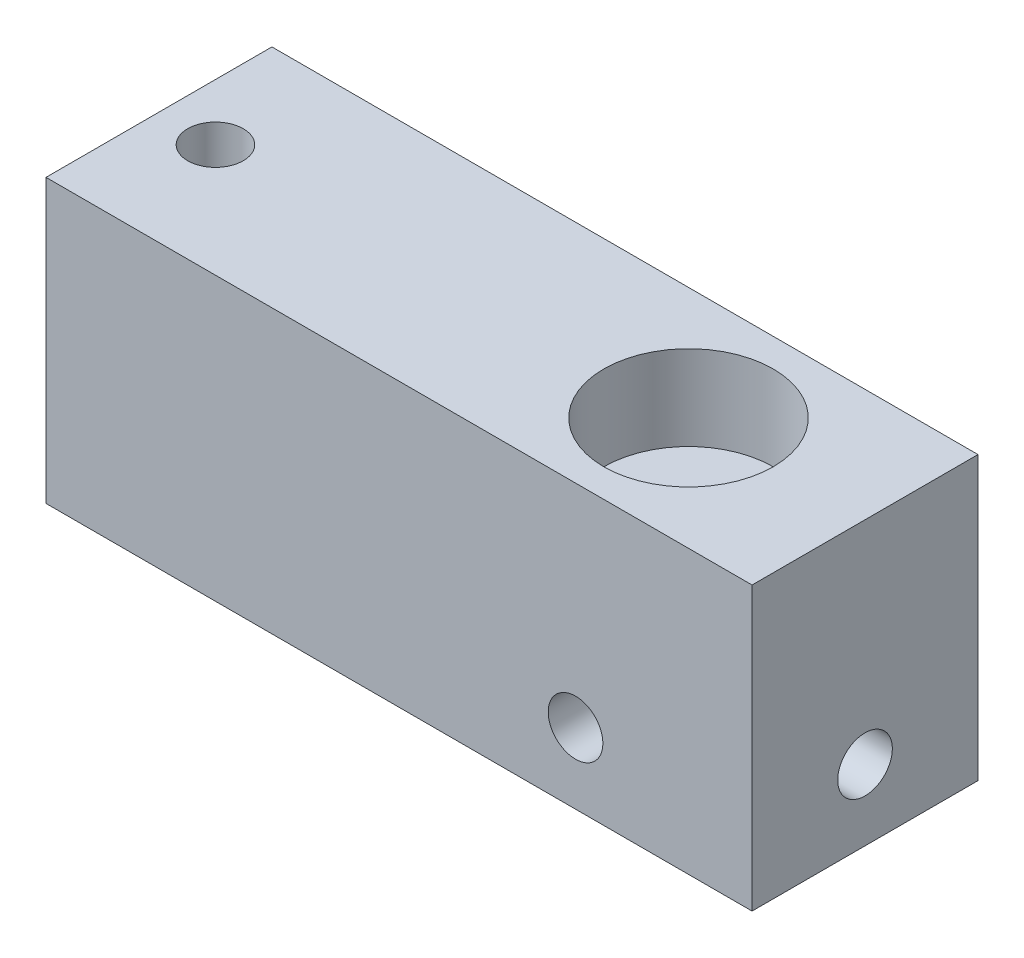
SolidWorks part; units mm, degrees
ref_plane "Front Plane" through (0, 0, 0) normal (0, 0, 1) x (1, 0, 0)
ref_plane "Top Plane" through (0, 0, 0) normal (0, 1, 0) x (1, 0, 0)
ref_plane "Right Plane" through (0, 0, 0) normal (1, 0, 0) x (0, 0, -1)
sketch "Sketch1" plane through (0, 0, 0) normal (0, 0, 1) x (1, 0, 0)
  line L1 (-48.5353, 3.7388) -> (14.9647, 3.7388)
  line L2 (-48.5353, 3.7388) -> (-48.5353, -21.6612)
  line L3 (-48.5353, -21.6612) -> (14.9647, -21.6612)
  line L4 (14.9647, 3.7388) -> (14.9647, -21.6612)
  dimension "D1" = 63.5
  dimension "D2" = 25.4
extrude "Boss-Extrude1" add sketch "Sketch1" along normal blind 20.32
hole_wizard "#10 (0.1935) Diameter Hole1" positions "Sketch2" profile "Sketch3" hole size "#10" standard "ANSI Inch"
sketch "Sketch2" plane through (14.9647, 0, 0) normal (1, 0, 0) x (0, 0, -1)
  line L0 (-20.32, -21.6612) -> (-20.32, 3.7388) construction
  line L2 (-20.32, -21.6612) -> (0, -21.6612) construction
  point P0 (-10.16, -15.3112)
  dimension "D1" = 10.16
  dimension "D2" = 6.35
sketch "Sketch3" plane through (14.9647, -15.3112, 10.16) normal (0, 1, 0) x (0, 0, -1)
  line L0 (0, 0) -> (0, 17.3516)
  line L1 (0, 17.3516) -> (2.4574, 15.875)
  line L2 (2.4574, 15.875) -> (2.4574, 0)
  line L5 (2.4574, 0) -> (0, 0)
  line L10 (0, 17.3516) -> (-2.4575, 15.875) construction
  line L11 (0, -6.35) -> (0, 107.95) construction
  dimension "Hole Dia." = 4.9149
  dimension "Hole Depth" = 15.875
  dimension "Drill Angle" = 118
hole_wizard "#10 (0.1935) Diameter Hole2" positions "Sketch4" profile "Sketch5" hole size "#10" standard "ANSI Inch"
sketch "Sketch4" plane through (0, 0, 20.32) normal (0, 0, 1) x (1, 0, 0)
  line L0 (-48.5353, -21.6612) -> (14.9647, -21.6612) construction
  line L1 (14.9647, -21.6612) -> (14.9647, 3.7388) construction
  point P0 (-0.9103, -15.3112)
  dimension "D1" = 6.35
  dimension "D2" = 15.875
sketch "Sketch5" plane through (-0.9103, -15.3112, 20.32) normal (1, 0, 0) x (0, -1, 0)
  line L0 (0, 0) -> (0, 11.6366)
  line L1 (0, 11.6366) -> (2.4574, 10.16)
  line L2 (2.4574, 10.16) -> (2.4574, 0)
  line L5 (2.4574, 0) -> (0, 0)
  line L10 (0, 11.6366) -> (-2.4574, 10.16) construction
  line L11 (0, -6.35) -> (0, 107.95) construction
  dimension "Hole Dia." = 4.9149
  dimension "Hole Depth" = 10.16
  dimension "Drill Angle" = 118
sketch "Sketch6" plane through (0, -21.6612, 0) normal (0, -1, 0) x (-1, 0, 0)
  line L0 (48.5353, -20.32) -> (-14.9647, -20.32) construction
  line L1 (-14.9647, -20.32) -> (-14.9647, 0) construction
  circle A0 centre (0.9103, -10.16) radius 3.175
  point P6 (-5.8072, -10.6137)
  dimension "D1" = 6.35
  dimension "D2" = 10.16
  dimension "D3" = 15.875
extrude "Cut-Extrude1" cut sketch "Sketch6" against normal through all
sketch "Sketch7" plane through (0, 3.7388, 0) normal (0, 1, 0) x (1, 0, 0)
  line L0 (14.9647, -20.32) -> (14.9647, 0) construction
  line L1 (14.9647, 0) -> (-48.5353, 0) construction
  circle A0 centre (-0.9103, -10.16) radius 7.62
  point P6 (1.5154, -6.162)
  dimension "D3" = 15.24
  dimension "D1" = 15.875
  dimension "D2" = 10.16
extrude "Cut-Extrude2" cut sketch "Sketch7" against normal blind 7.62
hole_wizard "Tap Drill for M6x1.0 Tap1" positions "Sketch8" profile "Sketch9" hole size "M6x1.0" standard "ANSI Metric"
sketch "Sketch8" plane through (0, 3.7388, 0) normal (0, 1, 0) x (1, 0, 0)
  line L0 (14.9647, 0) -> (-48.5353, 0) construction
  line L1 (-48.5353, -20.32) -> (-48.5353, 0) construction
  point P0 (-43.4553, -10.16)
  dimension "D1" = 10.16
  dimension "D2" = 5.08
sketch "Sketch9" plane through (-43.4553, 3.7388, 10.16) normal (1, 0, 0) x (0, 0, 1)
  line L0 (0, 0) -> (0, 17.5042)
  line L1 (0, 17.5042) -> (2.5, 16.002)
  line L2 (2.5, 16.002) -> (2.5, 0)
  line L5 (2.5, 0) -> (0, 0)
  line L10 (0, 17.5042) -> (-2.5, 16.002) construction
  line L11 (0, -6.35) -> (0, 107.95) construction
  dimension "Hole Dia." = 5
  dimension "Hole Depth" = 16.002
  dimension "Drill Angle" = 118
